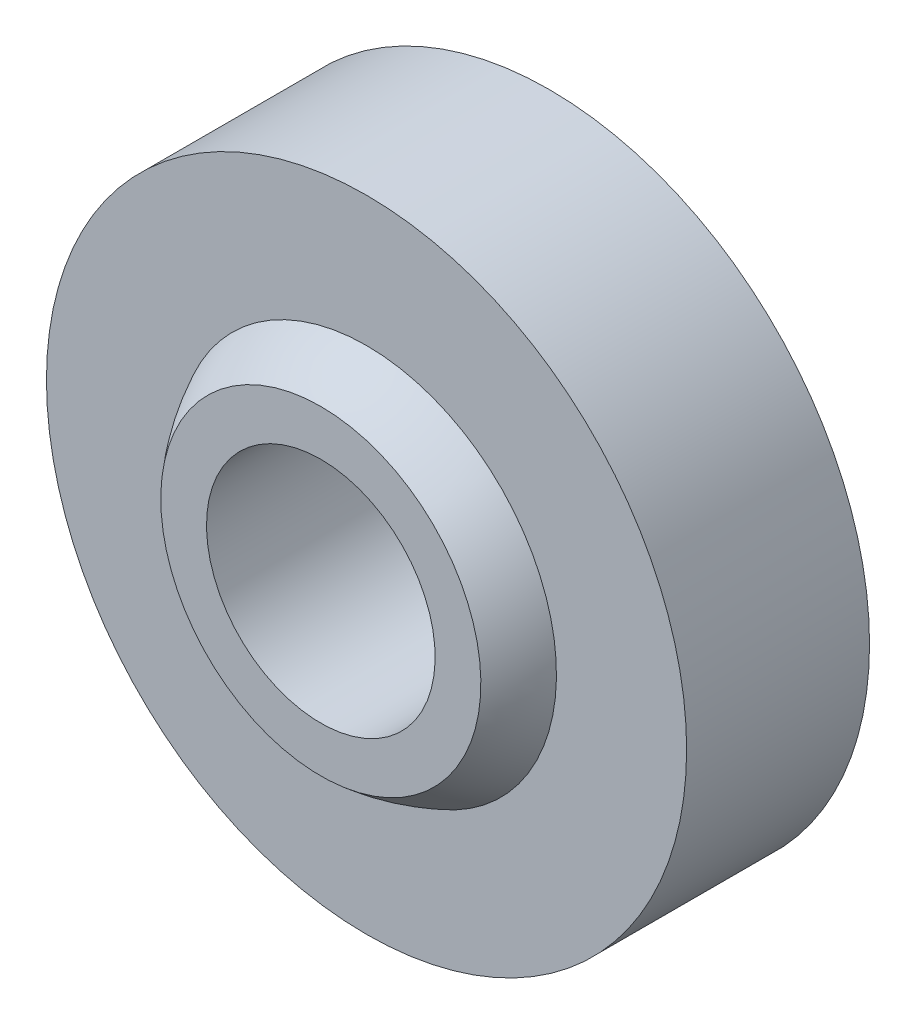
SolidWorks part; units mm, degrees
material "AISI 304"
ref_plane "前视基准面" through (0, 0, 0) normal (0, 0, 1) x (1, 0, 0)
ref_plane "上视基准面" through (0, 0, 0) normal (0, 1, 0) x (1, 0, 0)
ref_plane "右视基准面" through (0, 0, 0) normal (1, 0, 0) x (0, 0, -1)
other "Configuration Table"
sketch "草图1" plane through (0, 0, 0) normal (0, 0, 1) x (1, 0, 0)
  line L0 (-5.037, 0) -> (4.0741, 0) construction
  line L1 (0, 2.9259) -> (0, -3.9259) construction
  circle A0 centre (0, 0) radius 2.5
  circle A1 centre (0, 0) radius 7
  dimension "D1" = 5
  dimension "D2" = 14
extrude "凸台-拉伸1" add sketch "草图1" along normal mid plane 4
sketch "草图2" plane through (0, 0, 0) normal (1, 0, 0) x (0, 0, -1)
  line L0 (0, 0) -> (-3, 0) construction
  line L1 (3, 2.5) -> (-3, 2.5)
  line L2 (0, -2.5) -> (-3, -2.5)
  line L3 (0, 2.5) -> (0, -2.5) construction
  line L4 (-3, 2.5) -> (-3, 3.5)
  line L5 (-3, -2.5) -> (-3, -3.5)
  line L6 (-3, -2.5) -> (-3, -3.5)
  line L7 (0, -2.5) -> (-3, -2.5)
  line L8 (3, 2.5) -> (3, 3.5)
  arc A0 (-3, 3.5) -> (3, 3.5) centre (0, 0) cw
  arc A1 (-3, -3.5) -> (0, -4.6098) centre (0, 0) ccw
  arc A2 (-3, -3.5) -> (0, -4.6098) centre (0, 0) ccw
  point P11 (-3.1394, 3.5)
  point P12 (0, 0)
  dimension "D1" = 3
  dimension "D2" = 5
  dimension "D3" = 3
  dimension "D4" = 7
revolve "旋转1" add sketch "草图2" angle 360 about L0
